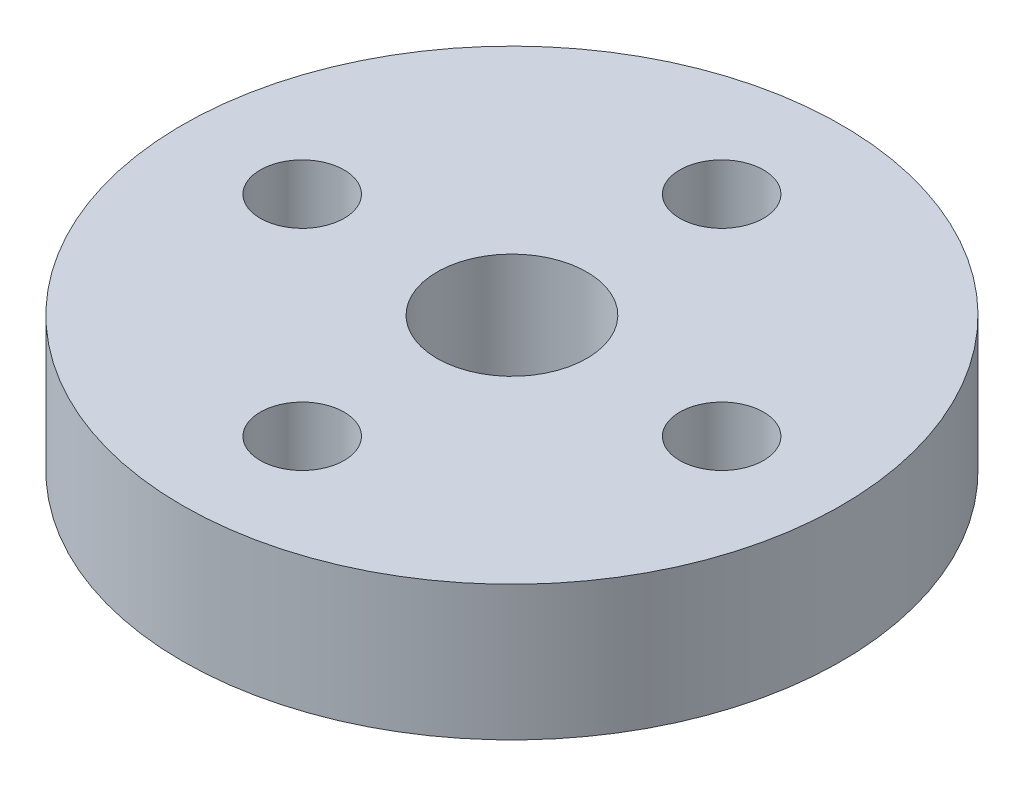
SolidWorks part; units mm, degrees
ref_plane "Front Plane" through (0, 0, 0) normal (0, 0, 1) x (1, 0, 0)
ref_plane "Top Plane" through (0, 0, 0) normal (0, 1, 0) x (1, 0, 0)
ref_plane "Right Plane" through (0, 0, 0) normal (1, 0, 0) x (0, 0, -1)
sketch "Sketch1" plane through (0, 0, 0) normal (0, 1, 0) x (1, 0, 0)
  circle A0 centre (0, 0) radius 11
  circle A1 centre (0, 0) radius 2.5
  circle A2 centre (0, 0) radius 7 construction
  circle A3 centre (0, 7) radius 1.4
  circle A4 centre (7, 0) radius 1.4
  circle A5 centre (0, -7) radius 1.4
  circle A6 centre (-7, 0) radius 1.4
  dimension "D1" = 5
  dimension "D2" = 14
  dimension "D3" = 22
  dimension "D4" = 2.8
extrude "Boss-Extrude1" add sketch "Sketch1" along normal blind 4.5
